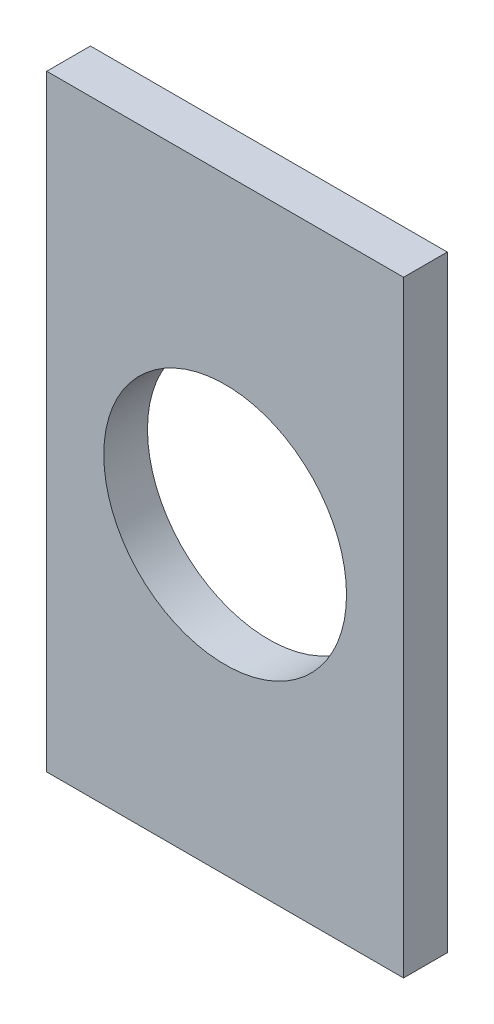
SolidWorks part; units mm, degrees
ref_plane "Front Plane" through (0, 0, 0) normal (0, 0, 1) x (1, 0, 0)
ref_plane "Top Plane" through (0, 0, 0) normal (0, 1, 0) x (1, 0, 0)
ref_plane "Right Plane" through (0, 0, 0) normal (1, 0, 0) x (0, 0, -1)
sketch "Sketch1" plane through (0, 0, 0) normal (0, 0, 1) x (1, 0, 0)
  line L1 (-7.35, -12.5) -> (7.35, -12.5)
  line L2 (-7.35, -12.5) -> (-7.35, 12.5)
  line L3 (-7.35, 12.5) -> (7.35, 12.5)
  line L4 (7.35, -12.5) -> (7.35, 12.5)
  line L5 (-7.35, -12.5) -> (7.35, 12.5) construction
  line L6 (-7.35, 12.5) -> (7.35, -12.5) construction
  circle A0 centre (0, 0) radius 5
  point P0 (0, 0)
  dimension "D3" = 10
  dimension "D1" = 25
  dimension "D2" = 14.7
extrude "Boss-Extrude1" add sketch "Sketch1" along normal mid plane 1.8
